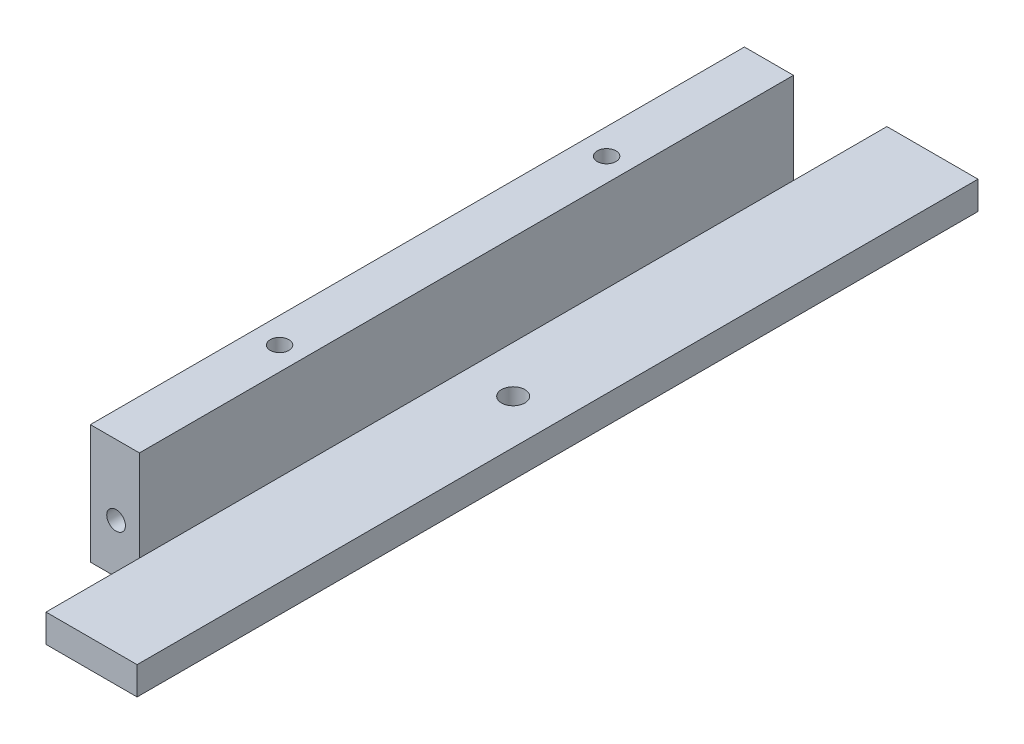
SolidWorks part; units mm, degrees
material "ABS"
ref_plane "Płaszczyzna przednia" through (0, 0, 0) normal (0, 0, 1) x (1, 0, 0)
ref_plane "Płaszczyzna górna" through (0, 0, 0) normal (0, 1, 0) x (1, 0, 0)
ref_plane "Płaszczyzna prawa" through (0, 0, 0) normal (1, 0, 0) x (0, 0, -1)
sketch "Szkic1" plane through (0, 0, 0) normal (0, 0, 1) x (1, 0, 0)
  line L0 (9.75, -9.75) -> (9.75, -15.75)
  line L1 (-9.75, -9.75) -> (9.75, -9.75)
  line L2 (-9.75, -9.75) -> (-9.75, 9.75)
  line L3 (-9.75, 9.75) -> (9.75, 9.75)
  line L4 (9.75, -9.75) -> (9.75, 9.75)
  line L5 (-9.75, -9.75) -> (9.75, 9.75) construction
  line L6 (-9.75, 9.75) -> (9.75, -9.75) construction
  line L7 (9.75, -15.75) -> (-20.25, -15.75)
  line L8 (-20.25, -15.75) -> (-20.25, 9.75)
  line L9 (-20.25, 9.75) -> (-9.75, 9.75)
  point P0 (0, 0)
  dimension "D1" = 19.5
  dimension "D2" = 30
  dimension "D3" = 6
extrude "Dodanie-wyciągnięcie1" add sketch "Szkic1" along normal blind 180
ref_plane "Płaszczyzna1" through (0, 0, 90) normal (0, 0, 1) x (1, 0, 0)
sketch "Szkic2" plane through (0, 9.75, 0) normal (0, 1, 0) x (1, 0, 0)
  line L0 (-9.75, -180) -> (-9.75, 0) construction
  line L1 (-20.25, -180) -> (-9.75, -180)
  line L2 (-20.25, -180) -> (-20.25, -160)
  line L3 (-20.25, -160) -> (-9.75, -160)
  line L4 (-9.75, -180) -> (-9.75, -160)
  dimension "D1" = 20
extrude "Wytnij-wyciągnięcie1" cut sketch "Szkic2" against normal through all
mirror "Lustro1" about plane through (0, 0, 90) normal (0, 0, 1) of "Wytnij-wyciągnięcie1"
sketch "Szkic3" plane through (0, 9.75, 0) normal (0, 1, 0) x (1, 0, 0)
  line L0 (-9.75, -160) -> (-9.75, -20) construction
  line L2 (-9.75, -20) -> (-20.25, -20) construction
  circle A0 centre (-14.75, -55) radius 2
  circle A1 centre (-14.75, -125) radius 2
  dimension "D1" = 4
  dimension "D2" = 5
  dimension "D3" = 70
  dimension "D4" = 35
extrude "Wytnij-wyciągnięcie2" cut sketch "Szkic3" against normal blind 10
sketch "Szkic4" plane through (0, 0, 160) normal (0, 0, 1) x (1, 0, 0)
  line L0 (-9.75, -9.75) -> (-9.75, 9.75) construction
  line L2 (-9.75, 9.75) -> (-20.25, 9.75) construction
  circle A0 centre (-14.75, -5.25) radius 2
  dimension "D1" = 4
  dimension "D2" = 5
  dimension "D3" = 15
extrude "Wytnij-wyciągnięcie3" cut sketch "Szkic4" against normal blind 10
mirror "Lustro2" about plane through (0, 0, 90) normal (0, 0, 1) of "Wytnij-wyciągnięcie3"
sketch "Szkic5" plane through (0, -9.75, 0) normal (0, 1, 0) x (1, 0, 0)
  circle A0 centre (0.25, -90) radius 2.5
  circle A1 centre (-14.75, -55) radius 2 construction
  circle A2 centre (-14.75, -55) radius 2 construction
  dimension "D1" = 15
  dimension "D2" = 35
  dimension "D3" = 5
extrude "Wytnij-wyciągnięcie4" cut sketch "Szkic5" against normal blind 10
